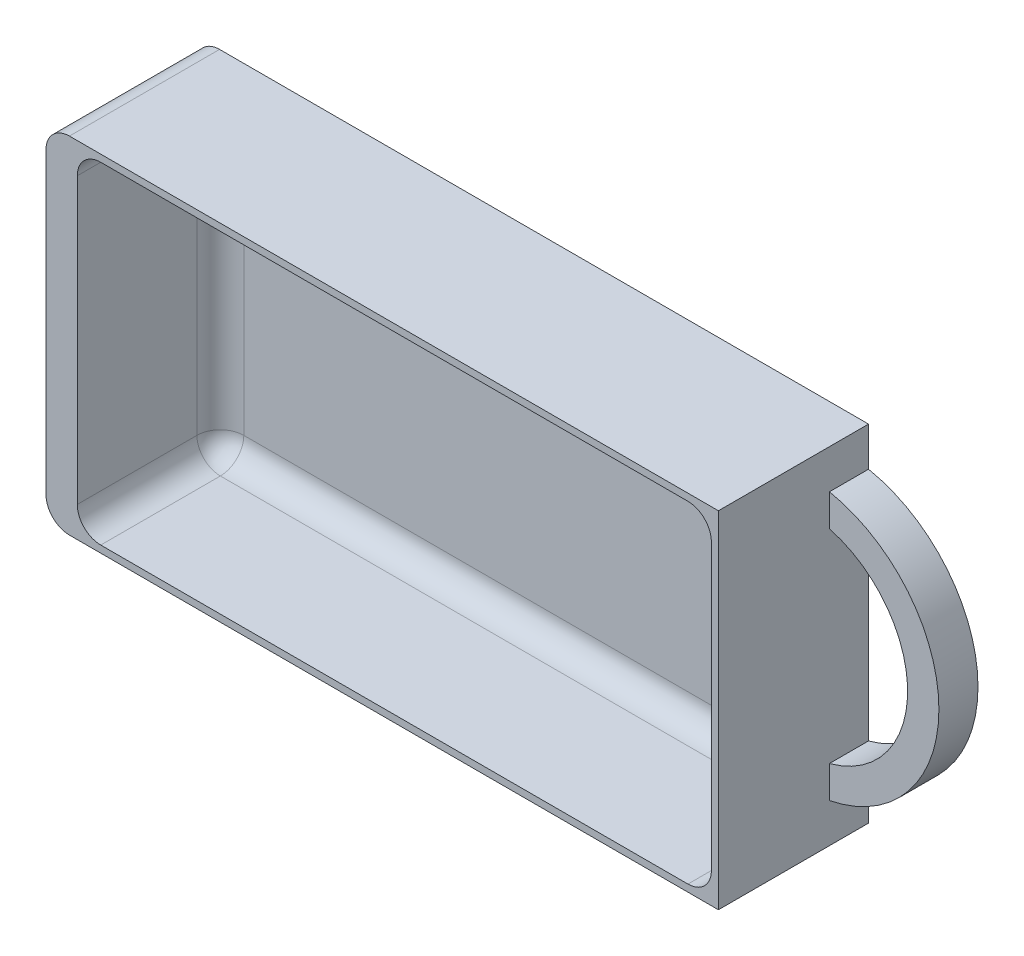
SolidWorks part; units mm, degrees
ref_plane "Спереди" through (0, 0, 0) normal (0, 0, 1) x (1, 0, 0)
ref_plane "Сверху" through (0, 0, 0) normal (0, 1, 0) x (1, 0, 0)
ref_plane "Справа" through (0, 0, 0) normal (1, 0, 0) x (0, 0, -1)
ref_plane "Плоскость4" through (0, 0, 9.6) normal (0, 0, 1) x (1, 0, 0)
sketch "Эскиз1" plane through (0, 0, 9.6) normal (0, 0, 1) x (1, 0, 0)
  line L0 (90, -22.1) -> (90, 22.1)
  line L1 (90, 22.1) -> (4, 22.1)
  line L2 (4, 22.1) -> (4, -22.1)
  line L3 (4, -22.1) -> (90, -22.1)
extrude "Бобышка-Вытянуть1" add sketch "Эскиз1" against normal blind 14.2
sketch "Эскиз2" plane through (0, 0, -4.6) normal (0, 0, -1) x (-1, 0, 0)
  line L0 (-90, -22.1) -> (-90, -17.1)
  line L1 (-90, 17.1) -> (-90, 22.1)
  line L2 (-90, 22.1) -> (-4, 22.1)
  line L3 (-4, 22.1) -> (-4, -22.1)
  line L4 (-4, -22.1) -> (-90, -22.1)
  line L5 (-90, -12.9948) -> (-90, 12.9948)
  arc A0 (-90, -17.1) -> (-90, 17.1) centre (-86.5568, 0) cw
  arc A1 (-90, 12.9948) -> (-90, -12.9948) centre (-86.5568, 0) ccw
extrude "Бобышка-Вытянуть2" add sketch "Эскиз2" along normal blind 5
sketch "Эскиз3" plane through (0, 0, 9.6) normal (0, 0, 1) x (1, 0, 0)
  line L0 (89.1, -21.2) -> (89.1, 21.2)
  line L1 (89.1, 21.2) -> (8, 21.2)
  line L2 (8, 21.2) -> (8, -21.2)
  line L3 (8, -21.2) -> (89.1, -21.2)
extrude "Вырез-Вытянуть1" cut sketch "Эскиз3" against normal blind 18.3
hole_wizard "Диаметр отверстия Ø8.3 (8.3)1" positions "Эскиз5" profile "Эскиз4" hole size "Ø8.3" standard "Ansi Metric"
sketch "Эскиз5" plane through (4, 0, 0) normal (-1, 0, 0) x (0, 0, 1)
  point P0 (0, 0)
sketch "Эскиз4" plane through (4, 0, 0) normal (0, 1, 0) x (0, 0, 1)
  line L0 (0, 0) -> (0, 3.2)
  line L1 (0, 3.2) -> (4.15, 3.2)
  line L2 (4.15, 3.2) -> (4.15, 0)
  line L5 (4.15, 0) -> (0, 0)
  line L10 (0, 3.2) -> (-4.15, 3.2) construction
  line L11 (0, -6.35) -> (0, 107.95) construction
  dimension "Диаметр отверстия" = 8.3
  dimension "Глубина отверстия" = 3.2
  dimension "Угол заточки сверла" = 180
fillet "Скругление1" radius 3 2 edges at (4, -22.1, 0) (4, 22.1, 0)
fillet "Скругление2" radius 3 1 edges at (48.55, -21.2, -8.7)
fillet "Скругление3" radius 3 1 edges at (48.55, 21.2, -8.7)
fillet "Скругление4" radius 3 5 edges at (8, -21.2, 1.95) (8, -20.3213, -7.8213) (8, 0, -8.7) (8, 21.2, 1.95) (8, 20.3213, -7.8213)
fillet "Скругление5" radius 3 5 edges at (89.1, -21.2, 1.95) (89.1, 0, -8.7) (89.1, -20.3213, -7.8213) (89.1, 21.2, 1.95) (89.1, 20.3213, -7.8213)
sketch "Эскиз6" plane through (4, 0, 0) normal (-1, 0, 0) x (0, 0, 1)
  circle A0 centre (0, 0) radius 4.15
  dimension "D1" = 8.3
extrude "Бобышка-Вытянуть3" add sketch "Эскиз6" against normal blind 3
